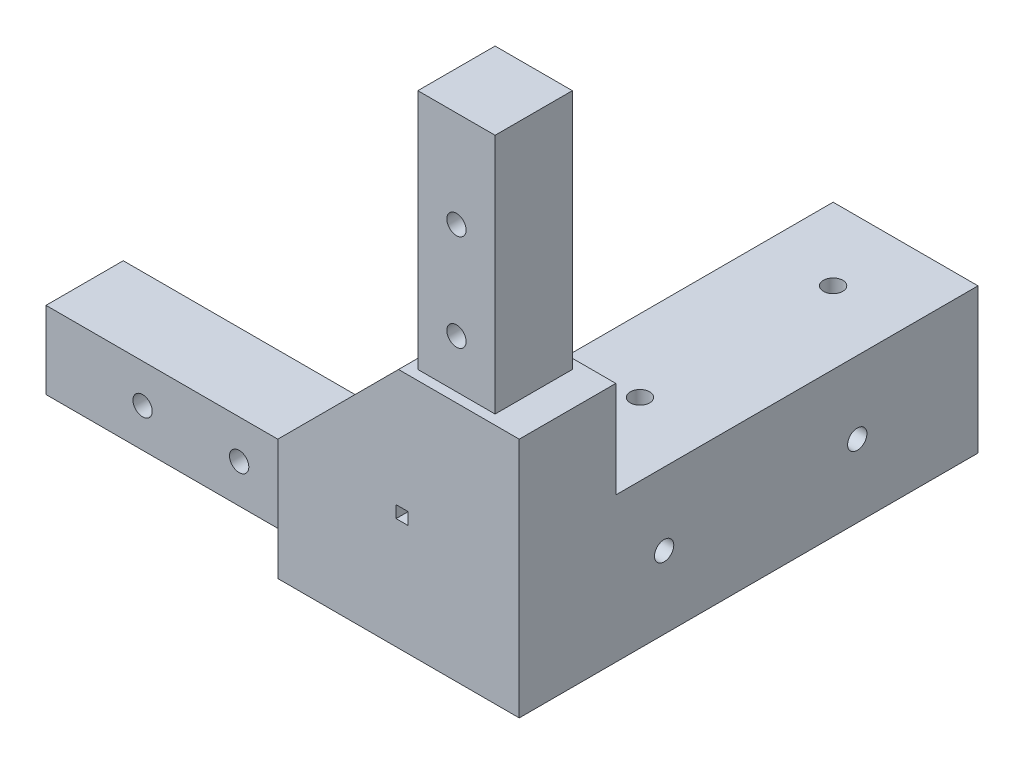
SolidWorks part; units mm, degrees
ref_plane "Front Plane" through (0, 0, 0) normal (0, 0, 1) x (1, 0, 0)
ref_plane "Top Plane" through (0, 0, 0) normal (0, 1, 0) x (1, 0, 0)
ref_plane "Right Plane" through (0, 0, 0) normal (1, 0, 0) x (0, 0, -1)
sketch "Sketch1" plane through (0, 0, 0) normal (0, 0, 1) x (1, 0, 0)
  line L1 (50, -50) -> (-50, -50)
  line L2 (50, -50) -> (50, 50)
  line L3 (50, 50) -> (-50, 50)
  line L4 (-50, -50) -> (-50, 50)
  line L5 (50, -50) -> (-50, 50) construction
  line L6 (50, 50) -> (-50, -50) construction
  point P0 (0, 0)
  dimension "D1" = 100
  dimension "D2" = 100
extrude "Boss-Extrude1" add sketch "Sketch1" against normal blind 100
sketch "Sketch5" plane through (0, 0, -100) normal (0, 0, -1) x (-1, 0, 0)
  line L0 (50, -50) -> (50, 50)
  line L1 (50, 50) -> (-50, 50)
  line L2 (-50, 50) -> (-50, -20)
  line L3 (-50, -50) -> (-50, 50) construction
  line L4 (-20, -20) -> (-50, -20)
  line L5 (50, -50) -> (-20, -50)
  line L8 (-20, -50) -> (-20, -20)
  dimension "D1" = 70
extrude "Cut-Extrude16" cut sketch "Sketch5" against normal blind 70
sketch "Sketch8" plane through (0, 0, -30) normal (0, 0, -1) x (-1, 0, 0)
  line L0 (-20, -20) -> (-20, 50)
  line L1 (50, 50) -> (-50, 50) construction
  line L2 (-20, 50) -> (50, 50)
  line L3 (50, 50) -> (50, -20)
  line L4 (50, -50) -> (50, 50) construction
  line L5 (50, -20) -> (-20, -20)
extrude "Cut-Extrude17" cut sketch "Sketch8" against normal blind 30
sketch "Sketch9" plane through (0, 0, -100) normal (0, 0, -1) x (-1, 0, 0)
  line L3 (-24.5, -45.5) -> (-45.5, -45.5)
  line L4 (-24.5, -45.5) -> (-24.5, -24.5)
  line L5 (-24.5, -24.5) -> (-45.5, -24.5)
  line L6 (-45.5, -45.5) -> (-45.5, -24.5)
  point P8 (-35, -35)
  dimension "D1" = 21
extrude "Cut-Extrude20" cut sketch "Sketch9" against normal blind 90
sketch "Sketch10" plane through (-50, 0, 0) normal (-1, 0, 0) x (0, 0, 1)
  line L3 (-23, -27) -> (-7, -27)
  line L4 (-23, -27) -> (-23, -43)
  line L5 (-23, -43) -> (-7, -43)
  line L6 (-7, -27) -> (-7, -43)
  line L9 (0, -50) -> (-30, -50)
  line L10 (0, -50) -> (0, -20)
  line L11 (0, -20) -> (-30, -20)
  line L12 (-30, -50) -> (-30, -20)
  point P8 (-15, -35)
  point P13 (-15, -35)
  dimension "D1" = 16
extrude "Cut-Extrude21" cut sketch "Sketch10" against normal blind 50
sketch "Sketch11" plane through (0, 0, 0) normal (-1, 0, 0) x (0, 0, 1)
  line L3 (-25, -25) -> (-5, -25)
  line L4 (-25, -25) -> (-25, -45)
  line L5 (-25, -45) -> (-5, -45)
  line L6 (-5, -25) -> (-5, -45)
  line L9 (0, -50) -> (-30, -50)
  line L10 (0, -50) -> (0, -20)
  line L11 (0, -20) -> (-30, -20)
  line L12 (-30, -50) -> (-30, -20)
  point P8 (-15, -35)
  point P13 (-15, -35)
  dimension "D1" = 20
extrude "Cut-Extrude22" cut sketch "Sketch11" against normal blind 20
sketch "Sketch12" plane through (0, 50, 0) normal (0, 1, 0) x (1, 0, 0)
  line L0 (20, 30) -> (50, 0) construction
  line L1 (50, 30) -> (20, 0) construction
  line L3 (25, 25) -> (45, 25)
  line L4 (25, 25) -> (25, 5)
  line L5 (25, 5) -> (45, 5)
  line L6 (45, 25) -> (45, 5)
  line L7 (25, 25) -> (45, 5) construction
  line L8 (25, 5) -> (45, 25) construction
  line L9 (20, 30) -> (50, 30)
  line L10 (20, 30) -> (20, 0)
  line L11 (20, 0) -> (50, 0)
  line L12 (50, 30) -> (50, 0)
  line L13 (20, 30) -> (50, 0) construction
  line L14 (20, 0) -> (50, 30) construction
  point P8 (35, 15)
  point P13 (35, 15)
  dimension "D1" = 20
extrude "Cut-Extrude23" cut sketch "Sketch12" against normal blind 70
sketch "Sketch13" plane through (0, 50, 0) normal (0, 1, 0) x (1, 0, 0)
  line L0 (25, 25) -> (45, 5) construction
  line L1 (45, 25) -> (25, 5) construction
  line L3 (27, 23) -> (43, 23)
  line L4 (27, 23) -> (27, 7)
  line L5 (27, 7) -> (43, 7)
  line L6 (43, 23) -> (43, 7)
  line L7 (27, 23) -> (43, 7) construction
  line L8 (27, 7) -> (43, 23) construction
  line L9 (25, 25) -> (45, 25)
  line L10 (25, 25) -> (25, 5)
  line L11 (25, 5) -> (45, 5)
  line L12 (45, 25) -> (45, 5)
  line L13 (25, 25) -> (45, 5) construction
  line L14 (25, 5) -> (45, 25) construction
  point P8 (35, 15)
  point P13 (35, 15)
  dimension "D1" = 16
extrude "Cut-Extrude24" cut sketch "Sketch13" against normal blind 50
sketch "Sketch15" plane through (0, -20, 0) normal (0, 1, 0) x (1, 0, 0)
  line L0 (35, 100) -> (35, 85) construction
  line L1 (50, 100) -> (20, 100) construction
  line L2 (35, 85) -> (35, 45) construction
  circle A0 centre (35, 85) radius 2
  circle A1 centre (35, 45) radius 2
  dimension "D2" = 40
  dimension "D1" = 15
extrude "Cut-Extrude25" cut sketch "Sketch15" against normal blind 30
sketch "Sketch16" plane through (50, 0, 0) normal (1, 0, 0) x (0, 0, -1)
  circle A0 centre (75, -35) radius 2
  circle A1 centre (35, -35) radius 2
  dimension "D2" = 40
extrude "Cut-Extrude26" cut sketch "Sketch16" against normal blind 30
sketch "Sketch17" plane through (0, 0, -23) normal (0, 0, -1) x (-1, 0, 0)
  line L2 (-35, 30) -> (-35, 10) construction
  circle A0 centre (-35, 30) radius 2
  circle A1 centre (-35, 10) radius 2
  dimension "D2" = 0
extrude "Cut-Extrude27" cut sketch "Sketch17" against normal blind 16
sketch "Sketch18" plane through (0, 0, -23) normal (0, 0, -1) x (-1, 0, 0)
  circle A0 centre (30, -35) radius 2
  circle A1 centre (10, -35) radius 2
  dimension "D2" = 20
extrude "Cut-Extrude29" cut sketch "Sketch18" against normal blind 16
sketch "Sketch19" plane through (0, 0, 0) normal (0, 0, 1) x (1, 0, 0)
  line L0 (20, -20) -> (50, -50) construction
  line L2 (20, -50) -> (50, -50)
  line L3 (20, -50) -> (20, -20)
  line L4 (20, -20) -> (50, -20)
  line L5 (50, -50) -> (50, -20)
  line L6 (20, -50) -> (50, -20) construction
  line L7 (20, -20) -> (50, -50) construction
  point P4 (35, -35)
extrude "Cut-Extrude30" cut sketch "Sketch19" against normal blind 5
sketch "Sketch20" plane through (0, 0, -5) normal (0, 0, 1) x (1, 0, 0)
  line L0 (25, 0) -> (0, -25)
  line L1 (0, -25) -> (0, -27)
  line L2 (0, -45) -> (0, -25) construction
  line L3 (25, 0) -> (27, 0)
  line L4 (25, 0) -> (45, 0) construction
  line L5 (27, 0) -> (27, -27)
  line L6 (27, -27) -> (0, -27)
  dimension "D1" = 2
  dimension "D2" = 2
extrude "Boss-Extrude2" add sketch "Sketch20" against normal blind 20
sketch "Sketch21" plane through (0, 0, 0) normal (-1, 0, 0) x (0, 0, 1)
  line L0 (-23, -43) -> (-25, -43) construction
  line L1 (-25, -25) -> (-25, -45) construction
  line L2 (-25, -43) -> (-25, -50) construction
  line L3 (-7, -43) -> (-5, -43) construction
  line L4 (-5, -45) -> (-5, -25) construction
  line L6 (-5, -43) -> (-25, -43)
  line L7 (-5, -43) -> (-5, -50)
  line L8 (-5, -50) -> (-25, -50)
  line L9 (-25, -43) -> (-25, -50)
  dimension "D1" = 7
extrude "Boss-Extrude6" add sketch "Sketch21" against normal blind 24
sketch "Sketch22" plane through (0, 0, -25) normal (0, 0, -1) x (-1, 0, 0)
  line L0 (-27, -27) -> (-24.5, -24.5) construction
  line L1 (-24.5, -45.5) -> (-24.5, -24.5) construction
  line L2 (-24.5, -24.5) -> (-24.5, -27) construction
  line L3 (-24.5, -45.5) -> (-24.5, -27) construction
  line L4 (-27, -24.5) -> (-24.5, -24.5)
  line L5 (-27, -24.5) -> (-27, -27)
  line L6 (-27, -27) -> (-24.5, -27)
  line L7 (-24.5, -24.5) -> (-24.5, -27)
  line L8 (-27, -24.5) -> (-24.5, -27) construction
  line L9 (-27, -27) -> (-24.5, -24.5) construction
  line L10 (-27, -27) -> (-24.5, -27) construction
  point P7 (-25.75, -25.75)
extrude "Cut-Extrude31" cut sketch "Sketch22" against normal blind 20
sketch "Sketch23" plane through (0, 0, 0) normal (0, 1, 0) x (1, 0, 0)
  line L0 (43, 23) -> (43, 25) construction
  line L1 (45, 25) -> (25, 25) construction
  line L2 (43, 7) -> (43, 5) construction
  line L3 (25, 5) -> (45, 5) construction
  line L4 (43, 5) -> (50, 5) construction
  line L6 (50, 5) -> (43, 5)
  line L7 (50, 5) -> (50, 25)
  line L8 (50, 25) -> (43, 25)
  line L9 (43, 5) -> (43, 25)
  dimension "D1" = 7
extrude "Boss-Extrude7" add sketch "Sketch23" against normal blind 24
